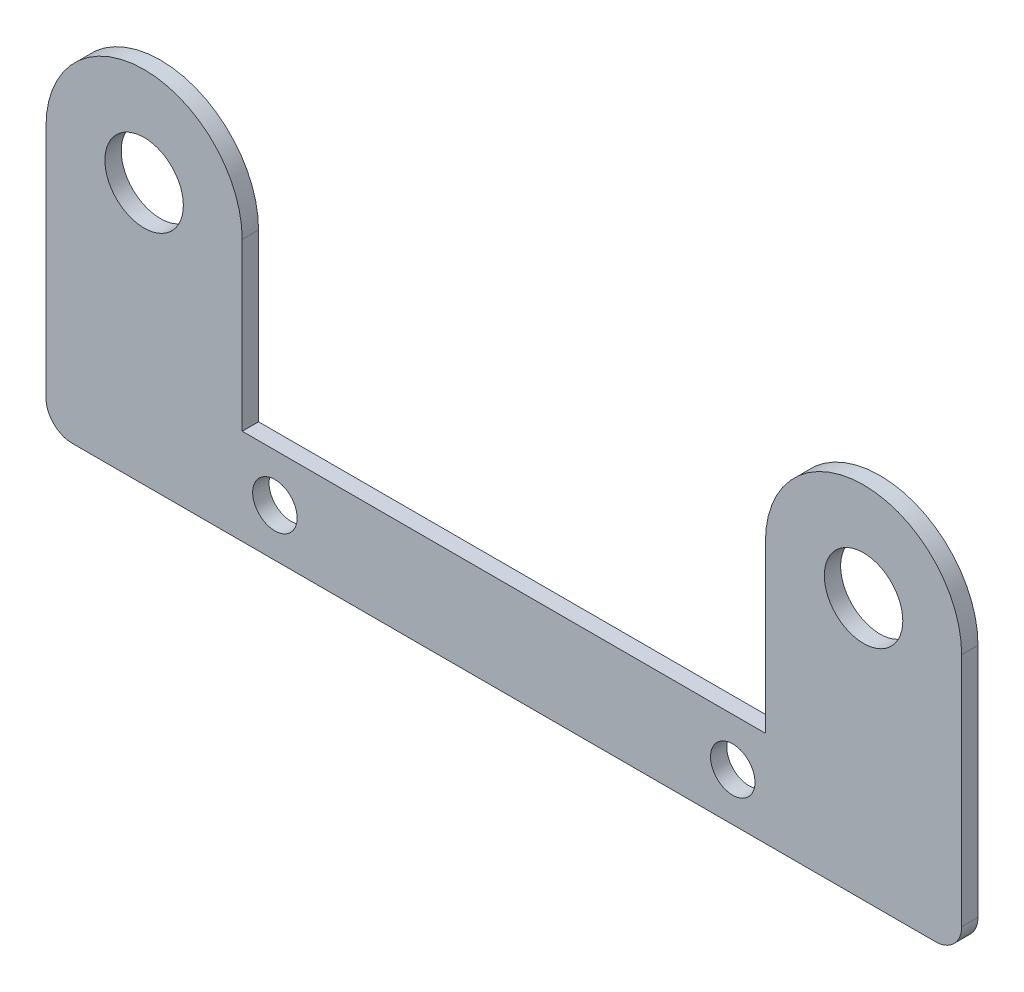
SolidWorks part; units mm, degrees
ref_plane "Front Plane" through (0, 0, 0) normal (0, 0, 1) x (1, 0, 0)
ref_plane "Top Plane" through (0, 0, 0) normal (0, 1, 0) x (1, 0, 0)
ref_plane "Right Plane" through (0, 0, 0) normal (1, 0, 0) x (0, 0, -1)
sketch "Sketch1" plane through (0, 0, 0) normal (0, 0, 1) x (1, 0, 0)
  line L0 (0, 25.4) -> (19.05, 25.4) construction
  line L2 (0, 25.4) -> (0, 0)
  line L3 (0, 0) -> (88.9, 0)
  line L4 (88.9, 25.4) -> (88.9, 0)
  line L5 (19.05, 25.4) -> (19.05, 9.271)
  line L6 (19.05, 9.271) -> (69.85, 9.271)
  line L7 (69.85, 9.271) -> (69.85, 25.4)
  line L8 (69.85, 25.4) -> (88.9, 25.4) construction
  line L10 (22.225, 4.6355) -> (66.675, 4.6355) construction
  line L11 (44.45, 9.271) -> (44.45, 0) construction
  circle A0 centre (22.225, 4.6355) radius 2.159
  circle A1 centre (66.675, 4.6355) radius 2.159
  circle A2 centre (9.525, 25.4) radius 3.81
  circle A3 centre (79.375, 25.4) radius 3.81
  arc A4 (0, 25.4) -> (19.05, 25.4) centre (9.525, 25.4) cw
  arc A5 (69.85, 25.4) -> (88.9, 25.4) centre (79.375, 25.4) cw
  point P0 (44.45, 4.6355)
  point P3 (59.436, 9.271)
  point P6 (0, 0)
  point P9 (19.05, 9.271)
  point P22 (19.05, 9.271)
  point P23 (59.436, 9.271)
  point P24 (17.018, 4.6355)
  dimension "D1" = 4.318
  dimension "D5" = 7.62
  dimension "D2" = 44.45
  dimension "D3" = 88.9
  dimension "D4" = 9.271
  dimension "D6" = 25.4
  dimension "D8" = 19.05
extrude "Boss-Extrude1" add sketch "Sketch1" along normal blind 1.5875
fillet "Fillet1" radius 2.54 2 edges at (88.9, 0, 0.7937) (0, 0, 0.7937)
